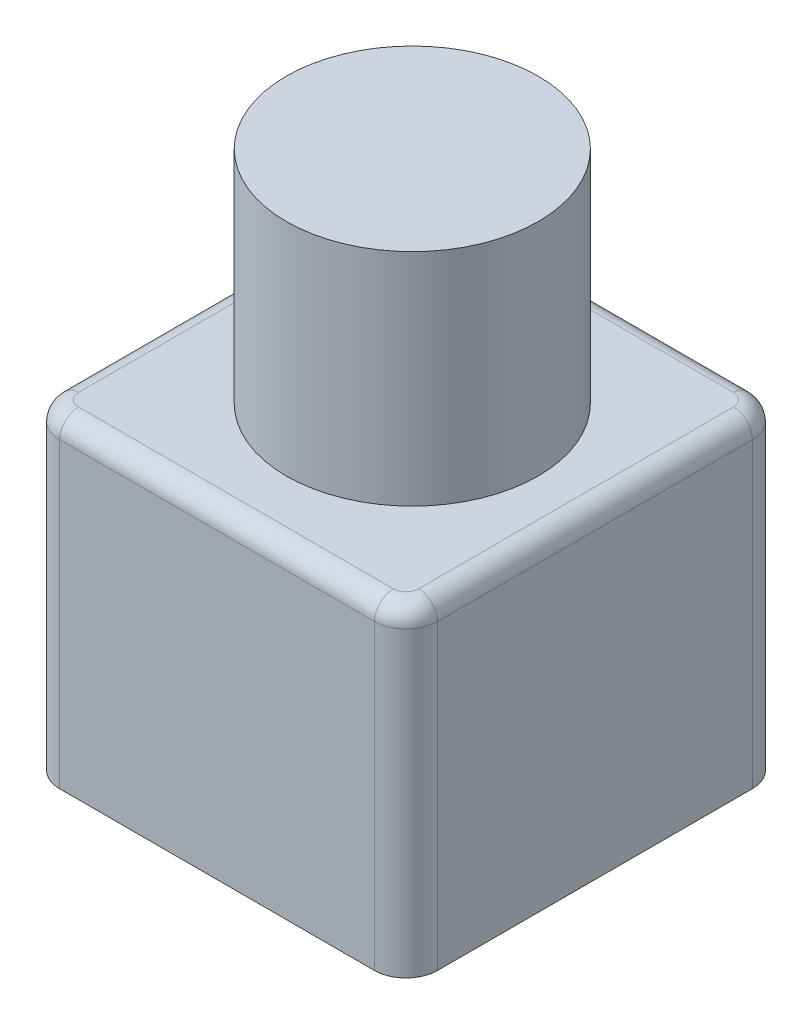
SolidWorks part; units mm, degrees
ref_plane "前基準面" through (0, 0, 0) normal (0, 0, 1) x (1, 0, 0)
ref_plane "上基準面" through (0, 0, 0) normal (0, 1, 0) x (1, 0, 0)
ref_plane "右基準面" through (0, 0, 0) normal (1, 0, 0) x (0, 0, -1)
sketch "草圖1" plane through (0, 0, 0) normal (0, 1, 0) x (1, 0, 0)
  line L1 (-30, 30) -> (30, 30)
  line L2 (-30, 30) -> (-30, -30)
  line L3 (-30, -30) -> (30, -30)
  line L4 (30, 30) -> (30, -30)
  line L5 (-30, 30) -> (30, -30) construction
  line L6 (-30, -30) -> (30, 30) construction
  point P0 (0, 0)
extrude "填料-伸長1" add sketch "草圖1" along normal blind 51
sketch "草圖2" plane through (0, 51, 0) normal (0, 1, 0) x (1, 0, 0)
  line L0 (-30, 30) -> (-30, -30) construction
  line L1 (30, 30) -> (-30, 30) construction
  circle A0 centre (1, 0) radius 20
  dimension "D1" = 31
  dimension "D2" = 30
extrude "填料-伸長2" add sketch "草圖2" along normal blind 35 contours A0
sketch "草圖4" plane through (-30, 0, 0) normal (-1, 0, 0) x (0, 0, 1)
  line L0 (30, 51) -> (30, 0) construction
  line L1 (-15, 45) -> (15, 45)
  line L2 (-15, 45) -> (-15, 20)
  line L3 (-15, 20) -> (15, 20)
  line L4 (15, 45) -> (15, 20)
  line L5 (-15, 45) -> (15, 20) construction
  line L6 (-15, 20) -> (15, 45) construction
  line L7 (-30, 51) -> (30, 51) construction
  point P0 (0, 32.5)
  dimension "D1" = 15
  dimension "D2" = 6
extrude "填料-伸長3" add sketch "草圖4" along normal blind 2
fillet "圓角4" radius 5 4 edges at (30, 25.5, -30) (30, 25.5, 30) (-30, 25.5, -30) (-30, 25.5, 30)
fillet "圓角5" radius 0.5 4 edges at (-32, 32.5, -15) (-32, 20, 0) (-32, 32.5, 15) (-32, 45, 0)
fillet "圓角6" radius 3 8 edges at (-28.5355, 51, -28.5355) (28.5355, 51, -28.5355) (28.5355, 51, 28.5355) (-28.5355, 51, 28.5355) (0, 51, -30) (30, 51, 0) (0, 51, 30) (-30, 51, 0)
